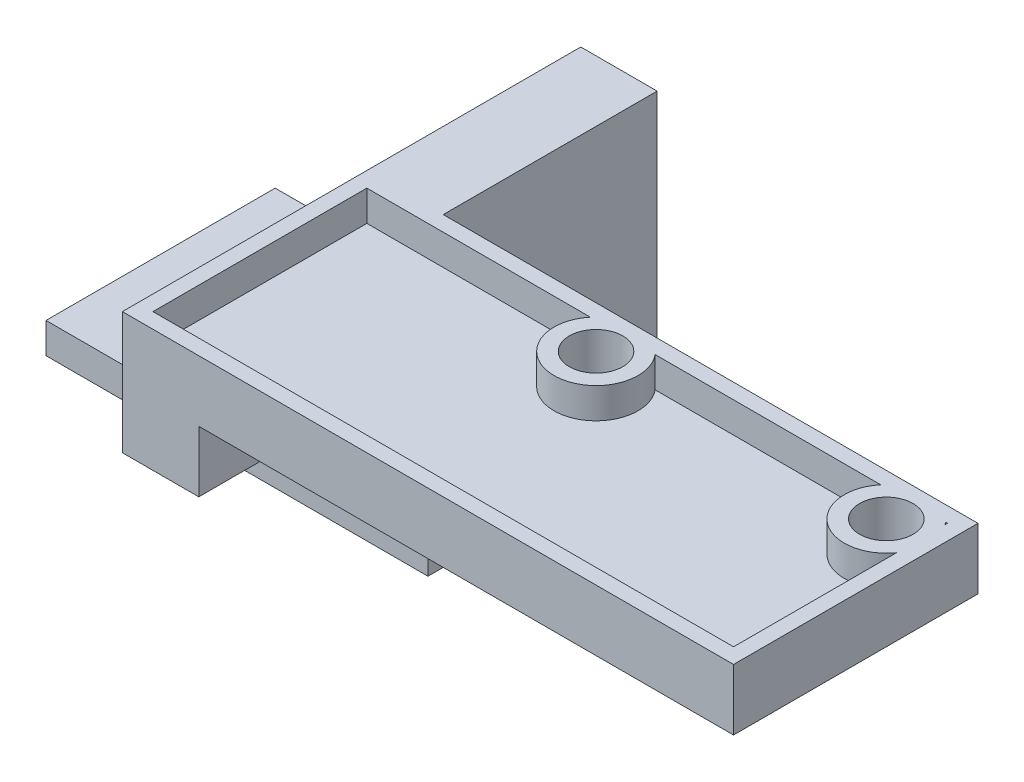
SolidWorks part; units mm, degrees
ref_plane "Front Plane" through (0, 0, 0) normal (0, 0, 1) x (1, 0, 0)
ref_plane "Top Plane" through (0, 0, 0) normal (0, 1, 0) x (1, 0, 0)
ref_plane "Right Plane" through (0, 0, 0) normal (1, 0, 0) x (0, 0, -1)
sketch "Sketch1" plane through (0, 0, 0) normal (0, 1, 0) x (1, 0, 0)
  line L1 (0, 0) -> (40, 0)
  line L2 (0, 0) -> (0, 16)
  line L3 (0, 16) -> (40, 16)
  line L4 (40, 0) -> (40, 16)
  dimension "D1" = 40
  dimension "D2" = 16
extrude "Boss-Extrude1" add sketch "Sketch1" along normal blind 2
sketch "Sketch2" plane through (0, 2, 0) normal (0, 1, 0) x (1, 0, 0)
  line L1 (0, 0) -> (40, 0)
  line L2 (0, 0) -> (0, 16)
  line L3 (0, 16) -> (40, 16)
  line L4 (40, 0) -> (40, 16)
  line L5 (1, 1) -> (39, 1)
  line L6 (1, 1) -> (1, 15)
  line L7 (1, 15) -> (39, 15)
  line L8 (39, 1) -> (39, 15)
  dimension "D1" = 1
  dimension "D2" = 1
  dimension "D3" = 14
  dimension "D4" = 38
extrude "Boss-Extrude2" add sketch "Sketch2" along normal blind 2
sketch "Sketch3" plane through (0, 4, 0) normal (0, 1, 0) x (1, 0, 0)
  line L0 (17.75, 13.25) -> (17.75, 16)
  line L1 (17.75, 16) -> (40, 16)
  line L2 (40, 16) -> (40, 0)
  line L3 (40, 0) -> (0.5, 0)
  line L4 (0.5, 0) -> (0.5, 16)
  line L5 (0.5, 16) -> (17.75, 16)
  line L6 (36.75, 16) -> (36.75, 13.25)
  line L7 (17.75, 13.25) -> (36.75, 13.25)
  line L8 (36.75, 13.25) -> (40, 13.25)
  line L9 (0, 0) -> (40, 0) construction
  line L10 (40, 0) -> (40, 16) construction
  circle A0 centre (36.75, 13.25) radius 1.75
  circle A1 centre (17.75, 13.25) radius 1.75
  circle A2 centre (17.75, 13.25) radius 2.75
  circle A3 centre (36.75, 13.25) radius 2.75
  line M18 (1, 15) -> (39, 15)
  line M19 (39, 15) -> (39, 1)
  dimension "D3" = 3.5
  dimension "D7" = 3.5
  dimension "D1" = 3.25
  dimension "D2" = 2.75
  dimension "D4" = 16
  dimension "D5" = 39.5
  dimension "D6" = 17.25
  dimension "D8" = 0
  dimension "D9" = 0
  dimension "D10" = 2.75
extrude "Boss-Extrude5" add sketch "Sketch3" against normal up to next contours L7 A0 L8 | L8 A0 L6 | L6 A0 L7 | L0 A1 L7 | L7 A1 L0 | A3 L6 M18 | A3 L8 M19 | L8 A3 M19 | L6 A3 M18 | A2 L0 M18 | L0 A2 M18
sketch "Sketch4" plane through (0, 4, 0) normal (0, 1, 0) x (1, 0, 0)
  circle A0 centre (17.75, 13.25) radius 1.75
  circle A1 centre (36.75, 13.25) radius 1.75
  dimension "D1" = 3.5
  dimension "D2" = 3.5
extrude "Cut-Extrude1" cut sketch "Sketch4" against normal through all
sketch "Sketch5" plane through (0, 0, 0) normal (0, -1, 0) x (-1, 0, 0)
  line L0 (0, 0) -> (-40, 0) construction
  line L1 (0, 16) -> (-5, 16)
  line L2 (0, 16) -> (0, 0)
  line L3 (0, 0) -> (-5, 0)
  line L4 (-5, 16) -> (-5, 0)
  dimension "D1" = 5
extrude "Boss-Extrude6" add sketch "Sketch5" along normal blind 16
sketch "Sketch6" plane through (0, -16, 0) normal (0, -1, 0) x (1, 0, 0)
  line L1 (5, 0) -> (0, 0)
  line L2 (5, 0) -> (5, -30)
  line L3 (5, -30) -> (0, -30)
  line L4 (0, 0) -> (0, -30)
  line L6 (0, -30) -> (0, -15)
  line L9 (0, -30) -> (-20, -30)
  line L10 (0, -30) -> (0, -15)
  line L11 (0, -15) -> (-20, -15)
  line L12 (-20, -30) -> (-20, -15)
  circle A0 centre (-10, -22.5) radius 2.6
  dimension "D4" = 5.2
  dimension "D1" = 15
  dimension "D2" = 5
  dimension "D3" = 15
  dimension "D5" = 20
  dimension "D6" = 10
  dimension "D7" = 7.5
extrude "Boss-Extrude7" add sketch "Sketch6" against normal blind 2
sketch "Sketch7" plane through (0, -14, 0) normal (0, 1, 0) x (1, 0, 0)
  line L1 (0, 15) -> (5, 15)
  line L2 (0, 15) -> (0, 16)
  line L3 (0, 16) -> (5, 16)
  line L4 (5, 15) -> (5, 16)
extrude "Boss-Extrude8" add sketch "Sketch7" along normal blind 2
sketch "Sketch9" plane through (5, 0, 0) normal (1, 0, 0) x (0, 0, -1)
  line L0 (30, -16) -> (0, -16) construction
  line L1 (11.8301, -16) -> (0, -16)
  line L2 (11.8301, -16) -> (11.8301, -8)
  line L3 (11.8301, -8) -> (0, -8)
  line L4 (0, -16) -> (0, -8)
  line L5 (0, -16) -> (0, 0) construction
extrude "Cut-Extrude3" cut sketch "Sketch9" against normal through all
sketch "Sketch10" plane through (0, 0, -16) normal (0, 0, -1) x (-1, 0, 0)
  line L0 (-5, -14) -> (-5, 0) construction
  line L1 (-5, 4) -> (0, 4)
  line L2 (-5, 4) -> (-5, -14)
  line L3 (-5, -14) -> (0, -14)
  line L4 (0, 4) -> (0, -14)
  line L5 (-40, 4) -> (0, 4) construction
  dimension "D1" = 0
extrude "Boss-Extrude9" add sketch "Sketch10" along normal up to surface (14 mm away) up to face at (-7.5, -15, -30)
sketch "Sketch11" plane through (5, 0, 0) normal (1, 0, 0) x (0, 0, -1)
  line L0 (0, -8) -> (0, 0) construction
  line L1 (11.8301, -16) -> (15.0001, -16)
  line L2 (11.8301, -16) -> (11.8301, -8)
  line L3 (11.8301, -8) -> (15.0001, -8)
  line L4 (15.0001, -16) -> (15.0001, -8)
  line L5 (15.0001, -8) -> (0, -8)
  line L6 (15.0001, -8) -> (15.0001, -4)
  line L7 (15.0001, -4) -> (0, -4)
  line L8 (0, -8) -> (0, -4)
  line M11 (0, 0) -> (0, -8)
  line M12 (0, -8) -> (11.8301, -8)
  line M13 (11.8301, -8) -> (11.8301, -16)
  line M14 (11.8301, -16) -> (30, -16)
  dimension "D1" = 3.17
  dimension "D2" = 8
extrude "Cut-Extrude4" cut sketch "Sketch11" against normal through all contours L6 L7 L3 M11 M12 | L4 L3 M14 M13
